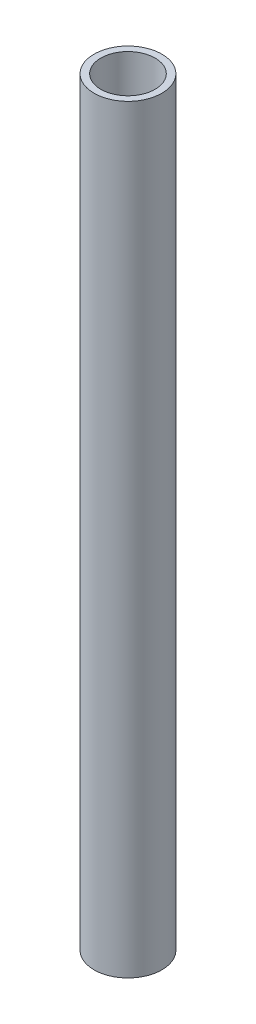
SolidWorks part; units mm, degrees
material "ABS"
ref_plane "Спереди" through (0, 0, 0) normal (0, 0, 1) x (1, 0, 0)
ref_plane "Сверху" through (0, 0, 0) normal (0, 1, 0) x (1, 0, 0)
ref_plane "Справа" through (0, 0, 0) normal (1, 0, 0) x (0, 0, -1)
sketch "Эскиз1" plane through (0, 0, 0) normal (0, 1, 0) x (1, 0, 0)
  circle A0 centre (0, 0) radius 1.25
  circle A1 centre (0, 0) radius 1
  dimension "D1" = 2.5
  dimension "D2" = 2
extrude "Бобышка-Вытянуть1" add sketch "Эскиз1" along normal blind 28
